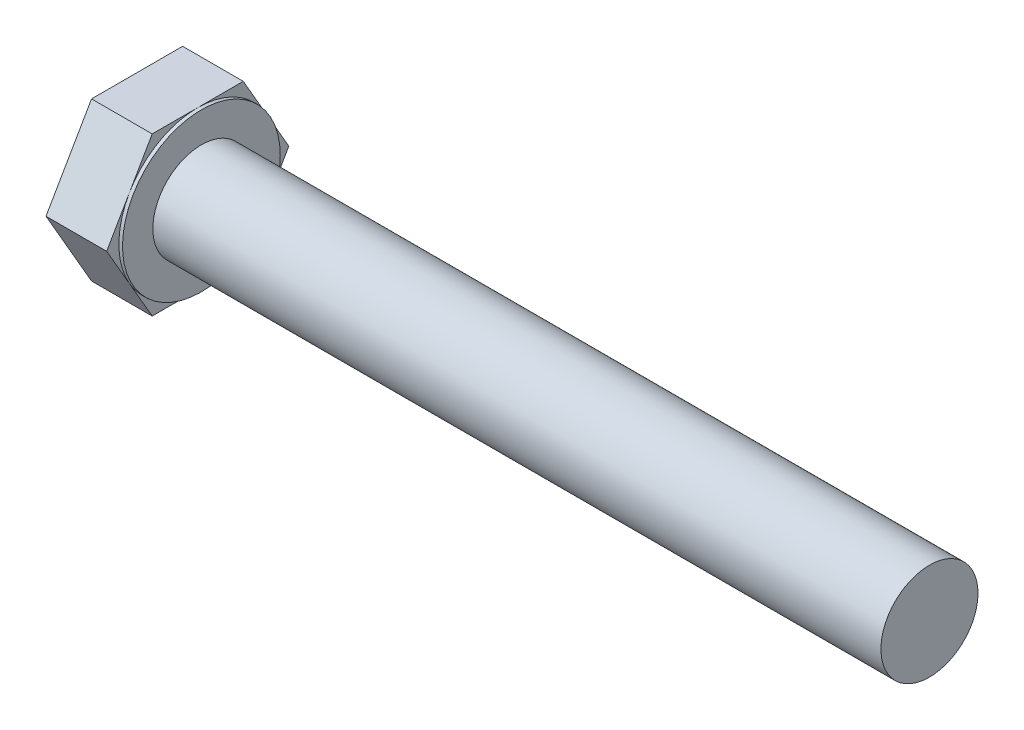
SolidWorks part; units mm, degrees
material "Plain Carbon Steel"
ref_plane "Front Plane" through (0, 0, 0) normal (0, 0, 1) x (1, 0, 0)
ref_plane "Top Plane" through (0, 0, 0) normal (0, 1, 0) x (1, 0, 0)
ref_plane "Right Plane" through (0, 0, 0) normal (1, 0, 0) x (0, 0, -1)
sketch "Sketch1" plane through (0, 0, 0) normal (1, 0, 0) x (0, 0, -1)
  line L1 (-7.5056, 0) -> (-3.7528, -6.5)
  line L2 (-3.7528, -6.5) -> (3.7528, -6.5)
  line L3 (3.7528, -6.5) -> (7.5056, 0)
  line L4 (7.5056, 0) -> (3.7528, 6.5)
  line L5 (3.7528, 6.5) -> (-3.7528, 6.5)
  line L6 (-3.7528, 6.5) -> (-7.5056, 0)
  circle A0 centre (0, 0) radius 6.5 construction
  dimension "D1" = 13
extrude "Boss-Extrude1" add sketch "Sketch1" against normal blind 5
sketch "Sketch2" plane through (0, 0, 0) normal (1, 0, 0) x (0, 0, -1)
  line L0 (3.7528, 6.5) -> (-3.7528, 6.5) construction
  circle A0 centre (0, 0) radius 6.5
extrude "Boss-Extrude2" add sketch "Sketch2" along normal blind 0.3
sketch "Sketch3" plane through (0.3, 0, 0) normal (1, 0, 0) x (0, 0, -1)
  circle A0 centre (0, 0) radius 4
  dimension "D1" = 8
extrude "Boss-Extrude3" add sketch "Sketch3" along normal blind 60
